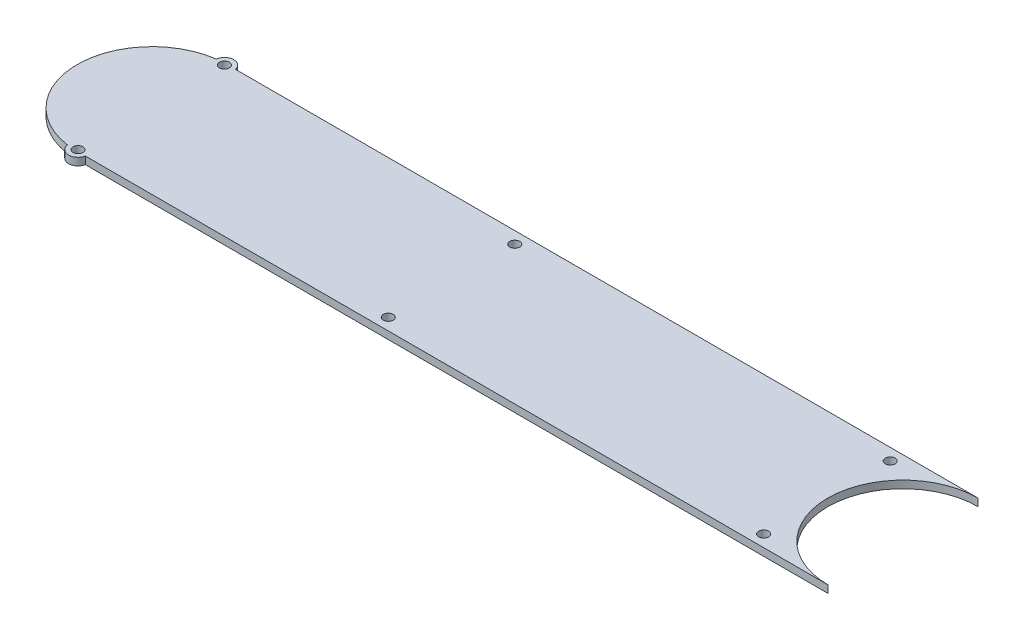
SolidWorks part; units mm, degrees
ref_plane "Front Plane" through (0, 0, 0) normal (0, 0, 1) x (1, 0, 0)
ref_plane "Top Plane" through (0, 0, 0) normal (0, 1, 0) x (1, 0, 0)
ref_plane "Right Plane" through (0, 0, 0) normal (1, 0, 0) x (0, 0, -1)
sketch "Sketch1" plane through (0, 0, 0) normal (0, 1, 0) x (1, 0, 0)
  line L0 (-110, 20) -> (90, 20)
  line L1 (-110, -20) -> (90, -20)
  circle A0 centre (90, 0) radius 20 construction
  arc A2 (90, 20) -> (90, -20) centre (90, 0) ccw
  circle A3 centre (-110, 0) radius 20 construction
  arc A4 (-110, 20) -> (-110, -20) centre (-110, 0) ccw
  dimension "D3" = 40
  dimension "D1" = 200
  dimension "D2" = 40
extrude "Boss-Extrude1" add sketch "Sketch1" along normal blind 2
sketch "Sketch3" plane through (0, 2, 0) normal (0, 1, 0) x (1, 0, 0)
  line L0 (-110, -20) -> (90, -20) construction
  line L1 (90, 20) -> (-110, 20) construction
  circle A0 centre (69.75, -16.85) radius 1.325
  circle A1 centre (69.75, 16.85) radius 1.325
  circle A2 centre (-30.25, -16.85) radius 1.325
  circle A3 centre (-30.25, 16.85) radius 1.325
  point P4 (78.5202, -20)
  point P9 (0, 0)
  point P14 (0, 0)
  point P17 (0, 0)
  point P18 (0, 0)
  dimension "D2" = 2.65
  dimension "D1" = 20.25
  dimension "D3" = 3.15
  dimension "D4" = 3.15
  dimension "D5" = 100
extrude "Cut-Extrude2" cut sketch "Sketch3" against normal blind 3
sketch "Sketch6" plane through (0, 2, 0) normal (0, 1, 0) x (1, 0, 0)
  line L0 (-110, -20) -> (90, -20) construction
  line L1 (90, 20) -> (-110, 20) construction
  circle A0 centre (-110.25, -19.5) radius 2.5
  circle A1 centre (-110.25, 19.5) radius 2.5
  circle A2 centre (-30.25, -16.85) radius 1.325 construction
  point P3 (0, 0)
  point P9 (0, 0)
  dimension "D2" = 5
  dimension "D1" = 0.5
  dimension "D3" = 0.5
  dimension "D4" = 80
extrude "Boss-Extrude2" add sketch "Sketch6" against normal blind 2
sketch "Sketch7" plane through (0, 2, 0) normal (0, 1, 0) x (1, 0, 0)
  circle A0 centre (-110.25, 19.5) radius 1.325
  circle A1 centre (-110.25, -19.5) radius 1.325
  point P5 (-110, -12.1962)
  point P6 (-110, -19.5)
  dimension "D1" = 2.65
extrude "Cut-Extrude3" cut sketch "Sketch7" against normal through all
